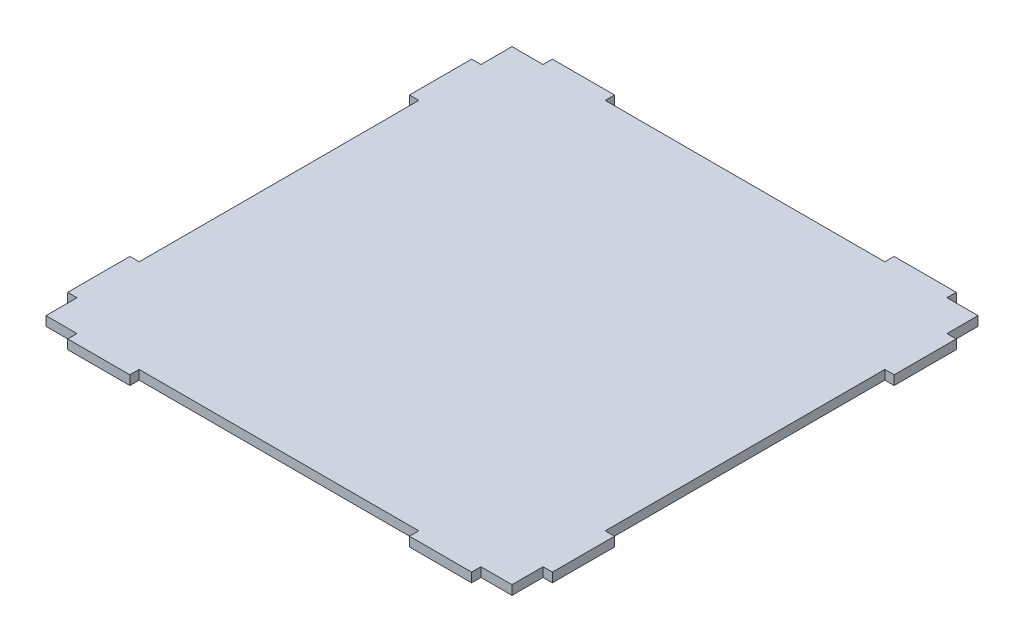
SolidWorks part; units mm, degrees
ref_plane "Front Plane" through (0, 0, 0) normal (0, 0, 1) x (1, 0, 0)
ref_plane "Top Plane" through (0, 0, 0) normal (0, 1, 0) x (1, 0, 0)
ref_plane "Right Plane" through (0, 0, 0) normal (1, 0, 0) x (0, 0, -1)
sketch "Sketch1" plane through (0, 0, 0) normal (0, 1, 0) x (1, 0, 0)
  line L1 (0, 0) -> (150, 0)
  line L2 (0, 0) -> (0, 150)
  line L3 (0, 150) -> (150, 150)
  line L4 (150, 0) -> (150, 150)
  dimension "D1" = 150
  dimension "D2" = 150
extrude "Boss-Extrude9" add sketch "Sketch1" along normal blind 3 contours L1 L4 L3 L2
sketch "Sketch8" plane through (0, 0, 0) normal (-1, 0, 0) x (0, 0, 1)
  line L0 (0, 3) -> (-150, 3) construction
  line L1 (-10, 3) -> (-30, 3)
  line L2 (-10, 3) -> (-10, 0)
  line L3 (-10, 0) -> (-30, 0)
  line L4 (-30, 3) -> (-30, 0)
  line L5 (0, 0) -> (-150, 0) construction
  dimension "D1" = 10
  dimension "D2" = 20
extrude "Boss-Extrude10" add sketch "Sketch8" along normal blind 3
sketch "Sketch9" plane through (0, 0, 0) normal (0, 0, 1) x (1, 0, 0)
  line L0 (0, 3) -> (150, 3) construction
  line L1 (10, 3) -> (30, 3)
  line L2 (10, 3) -> (10, 0)
  line L3 (10, 0) -> (30, 0)
  line L4 (30, 3) -> (30, 0)
  line L5 (0, 0) -> (150, 0) construction
  dimension "D1" = 10
  dimension "D2" = 20
extrude "Boss-Extrude11" add sketch "Sketch9" along normal blind 3
sketch "Sketch10" plane through (0, 0, 0) normal (0, 0, 1) x (1, 0, 0)
  line L0 (30, 3) -> (150, 3) construction
  line L1 (140, 3) -> (120, 3)
  line L2 (140, 3) -> (140, 0)
  line L3 (140, 0) -> (120, 0)
  line L4 (120, 3) -> (120, 0)
  line L5 (30, 0) -> (150, 0) construction
  dimension "D1" = 10
  dimension "D2" = 20
extrude "Boss-Extrude12" add sketch "Sketch10" along normal blind 3
sketch "Sketch11" plane through (150, 0, 0) normal (1, 0, 0) x (0, 0, -1)
  line L0 (0, 3) -> (150, 3) construction
  line L1 (10, 3) -> (30, 3)
  line L2 (10, 3) -> (10, 0)
  line L3 (10, 0) -> (30, 0)
  line L4 (30, 3) -> (30, 0)
  line L5 (0, 0) -> (150, 0) construction
  dimension "D1" = 10
  dimension "D2" = 20
extrude "Boss-Extrude13" add sketch "Sketch11" along normal blind 3
sketch "Sketch13" plane through (150, 0, 0) normal (1, 0, 0) x (0, 0, -1)
  line L0 (30, 3) -> (150, 3) construction
  line L1 (140, 3) -> (120, 3)
  line L2 (140, 3) -> (140, 0)
  line L3 (140, 0) -> (120, 0)
  line L4 (120, 3) -> (120, 0)
  line L5 (30, 0) -> (150, 0) construction
  dimension "D1" = 10
  dimension "D2" = 20
extrude "Boss-Extrude14" add sketch "Sketch13" along normal blind 3
sketch "Sketch14" plane through (0, 0, -150) normal (0, 0, -1) x (-1, 0, 0)
  line L0 (0, 3) -> (-150, 3) construction
  line L1 (-140, 3) -> (-120, 3)
  line L2 (-140, 3) -> (-140, 0)
  line L3 (-140, 0) -> (-120, 0)
  line L4 (-120, 3) -> (-120, 0)
  line L5 (0, 0) -> (-150, 0) construction
  dimension "D1" = 10
  dimension "D2" = 20
extrude "Boss-Extrude15" add sketch "Sketch14" along normal blind 3
sketch "Sketch15" plane through (0, 0, -150) normal (0, 0, -1) x (-1, 0, 0)
  line L0 (0, 3) -> (-120, 3) construction
  line L1 (-10, 3) -> (-30, 3)
  line L2 (-10, 3) -> (-10, 0)
  line L3 (-10, 0) -> (-30, 0)
  line L4 (-30, 3) -> (-30, 0)
  line L5 (0, 0) -> (-120, 0) construction
  dimension "D1" = 10
  dimension "D2" = 20
extrude "Boss-Extrude16" add sketch "Sketch15" along normal blind 3
sketch "Sketch16" plane through (0, 0, 0) normal (-1, 0, 0) x (0, 0, 1)
  line L0 (-30, 3) -> (-150, 3) construction
  line L1 (-140, 3) -> (-120, 3)
  line L2 (-140, 3) -> (-140, 0)
  line L3 (-140, 0) -> (-120, 0)
  line L4 (-120, 3) -> (-120, 0)
  line L5 (-30, 0) -> (-150, 0) construction
  dimension "D1" = 10
  dimension "D2" = 20
extrude "Boss-Extrude17" add sketch "Sketch16" along normal blind 3
